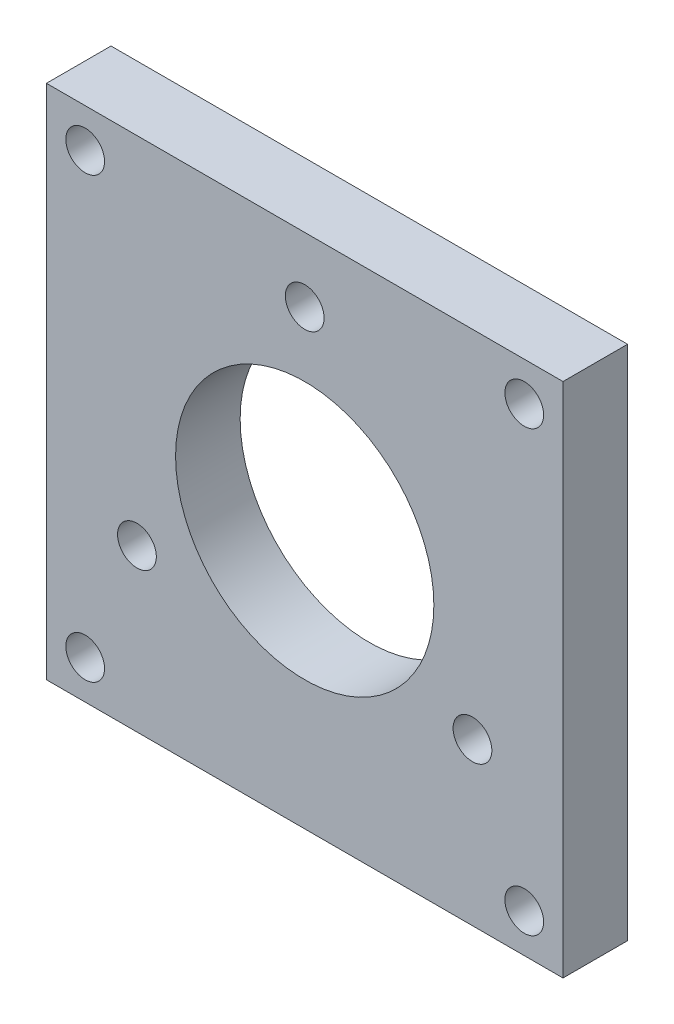
SolidWorks part; units mm, degrees
ref_plane "Front Plane" through (0, 0, 0) normal (0, 0, 1) x (1, 0, 0)
ref_plane "Top Plane" through (0, 0, 0) normal (0, 1, 0) x (1, 0, 0)
ref_plane "Right Plane" through (0, 0, 0) normal (1, 0, 0) x (0, 0, -1)
sketch "Sketch1" plane through (0, 0, 0) normal (0, 0, 1) x (1, 0, 0)
  line L1 (-20, -20) -> (20, -20)
  line L2 (-20, -20) -> (-20, 20)
  line L3 (-20, 20) -> (20, 20)
  line L4 (20, -20) -> (20, 20)
  line L5 (-20, -20) -> (20, 20) construction
  line L6 (-20, 20) -> (20, -20) construction
  dimension "D2" = 40
extrude "Boss-Extrude1" add sketch "Sketch1" along normal blind 5
sketch "Sketch2" plane through (0, 0, 0) normal (0, 0, -1) x (-1, 0, 0)
  circle A0 centre (0, 0) radius 10
  dimension "D1" = 20
extrude "Cut-Extrude1" cut sketch "Sketch2" against normal blind 5
sketch "Sketch3" plane through (0, 0, 0) normal (0, 0, -1) x (-1, 0, 0)
  circle A0 centre (0, 15) radius 1.5
  circle A1 centre (12.9904, -7.5) radius 1.5
  circle A2 centre (-12.9904, -7.5) radius 1.5
  point P9 (0, 0)
  dimension "D1" = 3
  dimension "D2" = 15
  dimension "D3" = 3
extrude "Cut-Extrude2" cut sketch "Sketch3" against normal blind 5
sketch "Sketch4" plane through (0, 0, 0) normal (0, 0, -1) x (-1, 0, 0)
  line L0 (-20, -20) -> (-20, 20) construction
  line L1 (-20, 20) -> (20, 20) construction
  line L2 (-20, 0) -> (20, 0) construction
  line L3 (0, -20) -> (0, 20) construction
  circle A1 centre (-17, 17) radius 1.5
  circle A2 centre (17, 17) radius 1.5
  circle A3 centre (17, -17) radius 1.5
  circle A4 centre (-17, -17) radius 1.5
  dimension "D2" = 3
  dimension "D3" = 3
  dimension "D4" = 3
extrude "Cut-Extrude3" cut sketch "Sketch4" against normal blind 5
